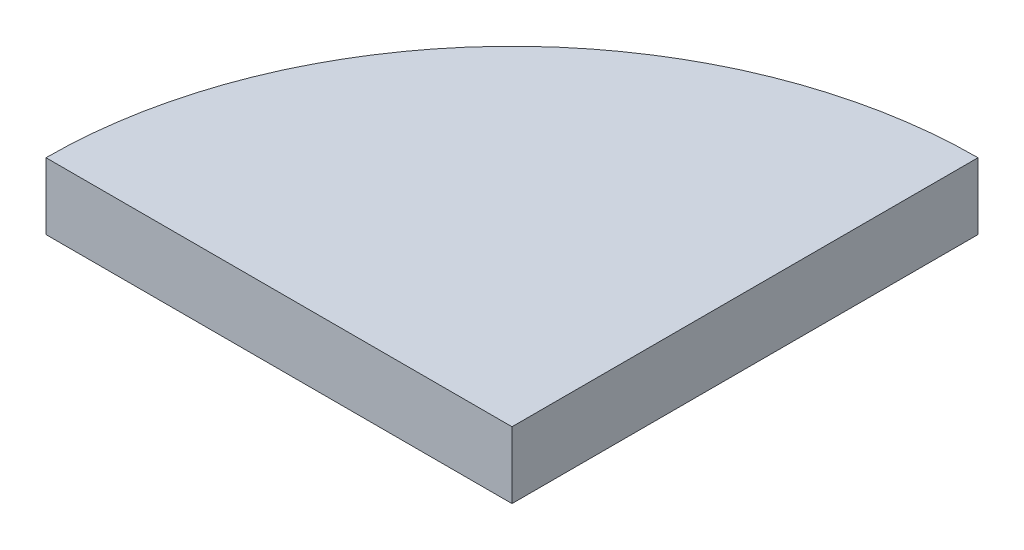
SolidWorks part; units mm, degrees
ref_plane "Front" through (0, 0, 0) normal (0, 0, 1) x (1, 0, 0)
ref_plane "Top" through (0, 0, 0) normal (0, 1, 0) x (1, 0, 0)
ref_plane "Right" through (0, 0, 0) normal (1, 0, 0) x (0, 0, -1)
sketch "Sketch1" plane through (0, 0, 0) normal (0, 1, 0) x (1, 0, 0)
  line L0 (-70, 0) -> (0, 0)
  line L1 (0, 0) -> (0, 70)
  arc A0 (-70, 0) -> (0, 70) centre (0, 0) cw
  dimension "D1" = 70
extrude "Boss-Extrude1" add sketch "Sketch1" along normal blind 10
